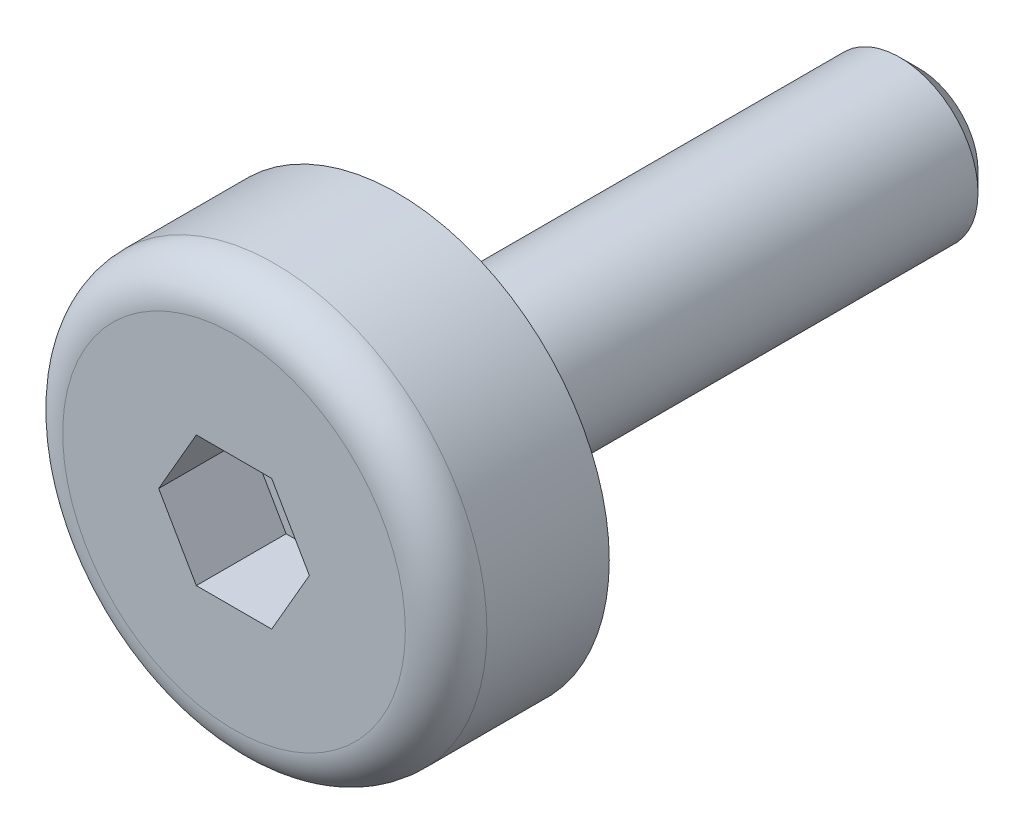
SolidWorks part; units mm, degrees
ref_plane "Front Plane" through (0, 0, 0) normal (0, 0, 1) x (1, 0, 0)
ref_plane "Top Plane" through (0, 0, 0) normal (0, 1, 0) x (1, 0, 0)
ref_plane "Right Plane" through (0, 0, 0) normal (1, 0, 0) x (0, 0, -1)
sketch "Screw Section" plane through (0, 0, 0) normal (0, 1, 0) x (1, 0, 0)
  line L0 (0, 8) -> (1.2, 8)
  line L1 (1.2, 8) -> (1.2, 0)
  line L2 (1.2, 0) -> (3.25, 0)
  line L3 (3.25, 0) -> (3.25, -2.5)
  line L4 (3.25, -2.5) -> (0, -2.5)
  line L5 (0, -2.5) -> (0, 8)
  line L6 (0, -10.123) -> (0, 10.123) construction
  dimension "D1" = 1.2
  dimension "D2" = 3.25
  dimension "D3" = 8
  dimension "D4" = 2.5
  dimension "D5" = 10.123
  dimension "D6" = 10.123
revolve "Screw Blank Revolve" add sketch "Screw Section" angle 360 about L6
chamfer "Shank Tip Chamfer" distance 0.3 1 edges at (1.2, 0, -8)
fillet "Pan Head Round" radius 0.625 1 edges at (3.25, 0, 2.5)
ref_plane "Head Crown Plane" through (0, 0, 2.5) normal (0, 0, 1) x (1, 0, 0)
sketch "Hex Drive Sketch" plane through (0, 0, 2.5) normal (0, 0, 1) x (1, 0, 0)
  line L1 (1.1547, 0) -> (0.5774, 1)
  line L2 (0.5774, 1) -> (-0.5774, 1)
  line L3 (-0.5774, 1) -> (-1.1547, 0)
  line L4 (-1.1547, 0) -> (-0.5774, -1)
  line L5 (-0.5774, -1) -> (0.5774, -1)
  line L6 (0.5774, -1) -> (1.1547, 0)
  circle A0 centre (0, 0) radius 1 construction
  dimension "D1" = 2
extrude "Hex Drive Cut" cut sketch "Hex Drive Sketch" against normal blind 1.375
equation "\"nominal_length\"= 8.0mm 'Screw length: under pan head or including flat head"
equation "\"model_shank_radius\"= 1.2mm 'Clearance envelope minor shank radius; thread is not modeled"
equation "\"head_diameter\"= 6.5mm 'Head outside diameter"
equation "\"head_height\"= 2.5mm 'Head axial height"
equation "\"drive_across_flats\"= 2mm 'Hex drive across flats"
equation "\"tip_chamfer\"= 0.3mm 'Shank tip chamfer"
equation "\"head_round\"= 0.625mm 'Pan head crown edge radius"
equation "\"drive_depth\"= 1.375mm 'Hex socket depth"
equation "\"axis_reference_halfspan\"= 10.123mm 'Half display length of the construction axis; avoids sharing a profile endpoint"
equation "\"D1@Screw Section\"= \"model_shank_radius\""
equation "\"D2@Screw Section\"= \"head_diameter\" / 2"
equation "\"D3@Screw Section\"= \"nominal_length\""
equation "\"D4@Screw Section\"= \"head_height\""
equation "\"D5@Screw Section\"= \"axis_reference_halfspan\""
equation "\"D6@Screw Section\"= \"axis_reference_halfspan\""
equation "\"full_turn\"= 360deg 'Full circular extent for revolves and patterns"
equation "\"D1@Screw Blank Revolve\"= \"full_turn\""
equation "\"D1@Shank Tip Chamfer\"= \"tip_chamfer\""
equation "\"D1@Pan Head Round\"= \"head_round\""
equation "\"D1@Head Crown Plane\"= \"head_height\""
equation "\"D1@Hex Drive Sketch\"= \"drive_across_flats\""
equation "\"D1@Hex Drive Cut\"= \"drive_depth\""
